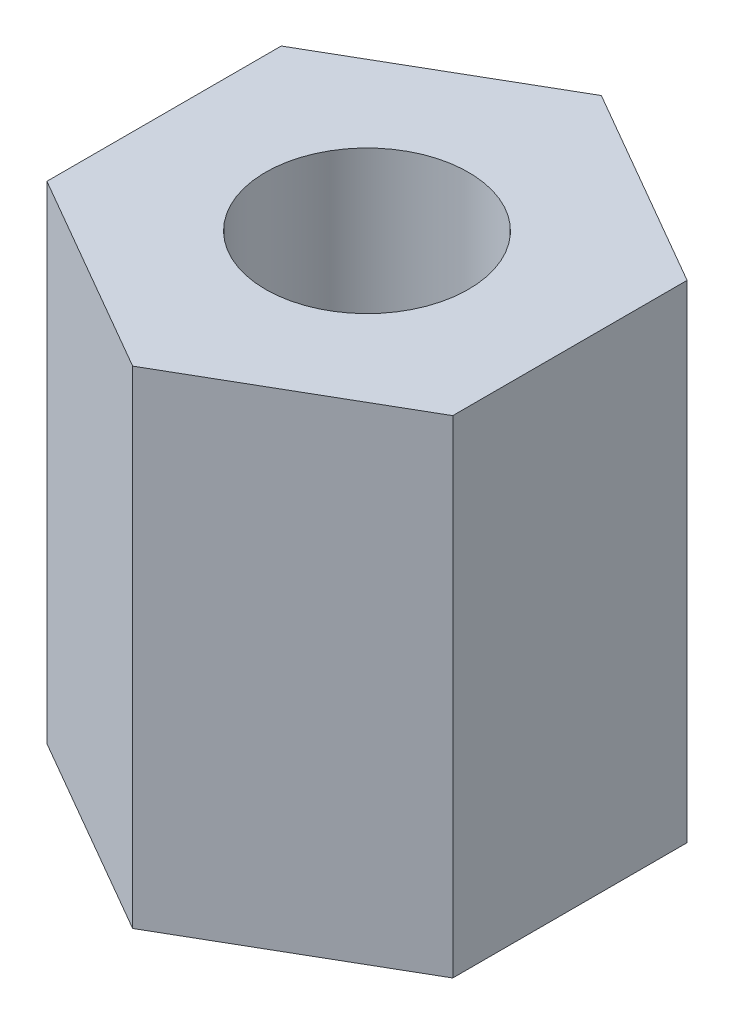
SolidWorks part; units mm, degrees
material "Brass"
ref_plane "Front Plane" through (0, 0, 0) normal (0, 0, 1) x (1, 0, 0)
ref_plane "Top Plane" through (0, 0, 0) normal (0, 1, 0) x (1, 0, 0)
ref_plane "Right Plane" through (0, 0, 0) normal (1, 0, 0) x (0, 0, -1)
sketch "Sketch1" plane through (0, 0, 0) normal (0, 1, 0) x (1, 0, 0)
  line L1 (0, 2.8868) -> (-2.5, 1.4434)
  line L2 (-2.5, 1.4434) -> (-2.5, -1.4434)
  line L3 (-2.5, -1.4434) -> (0, -2.8868)
  line L4 (0, -2.8868) -> (2.5, -1.4434)
  line L5 (2.5, -1.4434) -> (2.5, 1.4434)
  line L6 (2.5, 1.4434) -> (0, 2.8868)
  circle A0 centre (0, 0) radius 2.5 construction
  circle A1 centre (0, 0) radius 1.25
  dimension "D2" = 2.5
  dimension "D1" = 5
extrude "Boss-Extrude1" add sketch "Sketch1" along normal blind 6
